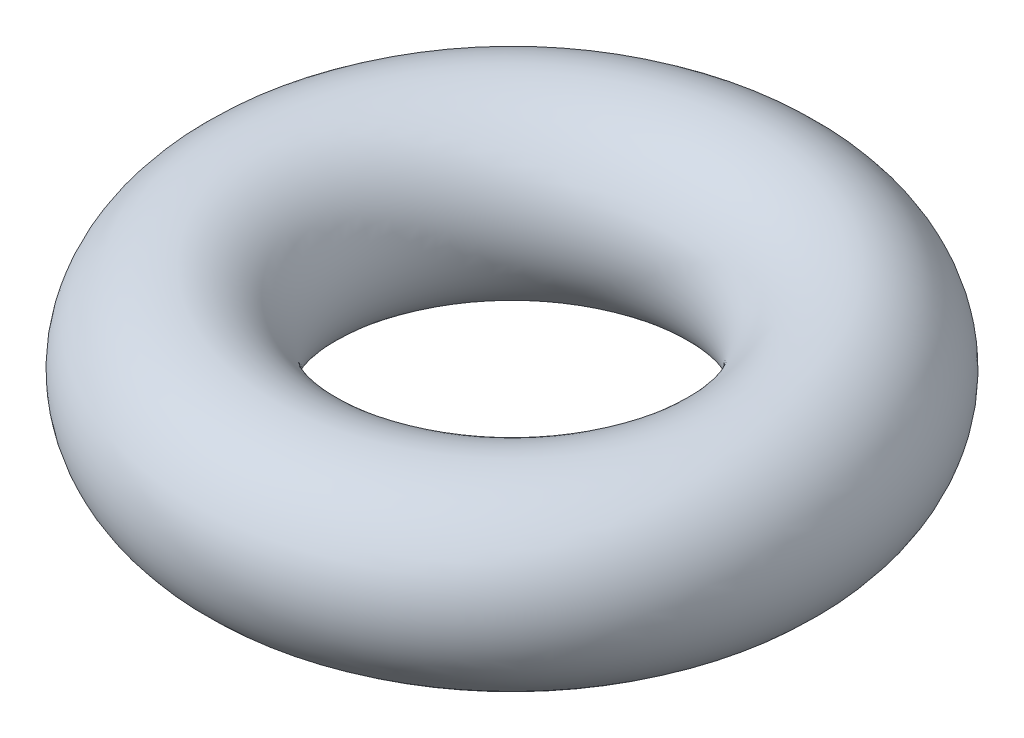
SolidWorks part; units mm, degrees
ref_plane "前视基准面" through (0, 0, 0) normal (0, 0, 1) x (1, 0, 0)
ref_plane "上视基准面" through (0, 0, 0) normal (0, 1, 0) x (1, 0, 0)
ref_plane "右视基准面" through (0, 0, 0) normal (1, 0, 0) x (0, 0, -1)
sketch "草图1" plane through (0, 0, 0) normal (0, 0, 1) x (1, 0, 0)
  line L0 (0, -27.1113) -> (0, 27.1113) construction
  circle A0 centre (-40, 0) radius 15
  point P2 (0, 0)
  dimension "D1" = 40
  dimension "D2" = 30
revolve "旋转1" add sketch "草图1" angle 360 about L0
